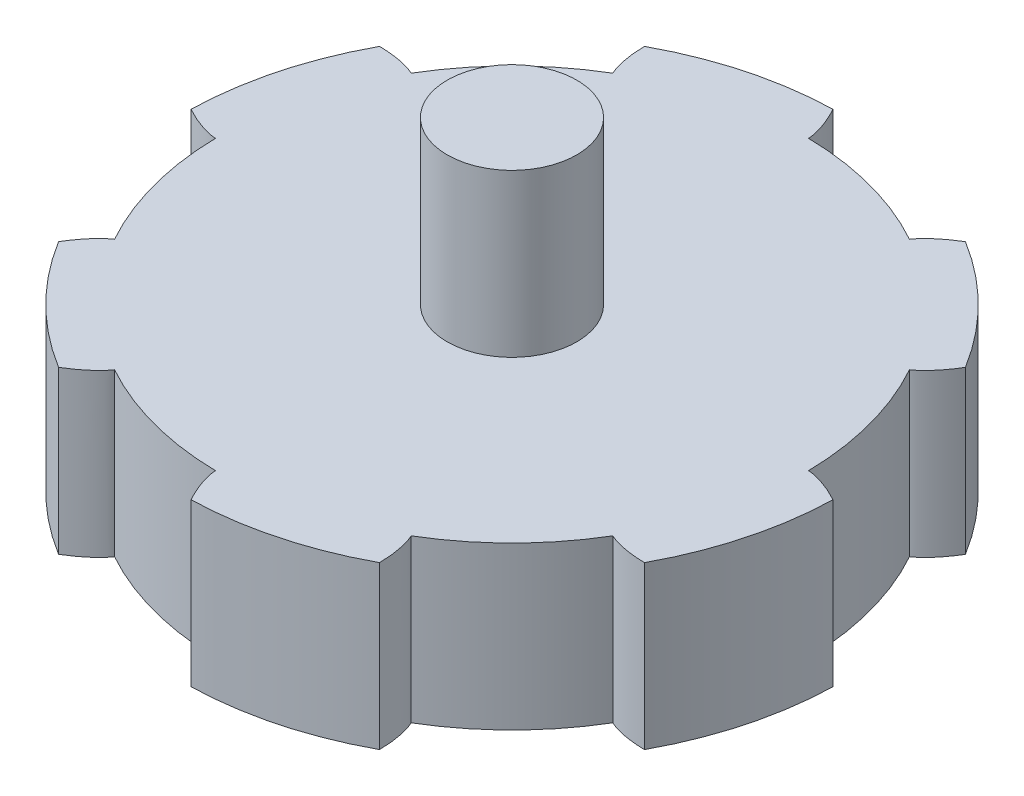
SolidWorks part; units mm, degrees
ref_plane "正面" through (0, 0, 0) normal (0, 0, 1) x (1, 0, 0)
ref_plane "平面" through (0, 0, 0) normal (0, 1, 0) x (1, 0, 0)
ref_plane "右側面" through (0, 0, 0) normal (1, 0, 0) x (0, 0, -1)
sketch "ｽｹｯﾁ1" plane through (0, 0, 0) normal (0, 1, 0) x (1, 0, 0)
  line L0 (0, 0) -> (0, 38.4) construction
  line L1 (-12.9461, 19.2) -> (11.294, 19.2) construction
  line L2 (-16.2445, 13.2875) -> (12.5124, 23.7541) construction
  line L3 (18.0421, 0) -> (19.2, 0) construction
  line L4 (19.2, 0) -> (20.3579, 0) construction
  circle A0 centre (0, 0) radius 19.2 construction
  circle A1 centre (0, 0) radius 18.0421
  circle A2 centre (0, 0) radius 20.3579 construction
  point P6 (0, 19.2)
  point P7 (0, 0)
  point P17 (-6.1708, 16.954)
  dimension "D1" = 38.4
  dimension "D2" = 20
sketch "ｽｹｯﾁ3" plane through (0, 0, 0) normal (0, 1, 0) x (1, 0, 0)
  line L0 (-6.1708, 16.954) -> (0, 19.2)
  line L1 (-7.1005, 16.5861) -> (-0.1443, 19.5641) construction
  line L2 (-8.0084, 16.1673) -> (-0.3318, 19.9699) construction
  line L3 (-8.8918, 15.6989) -> (-0.5675, 20.4137) construction
  line L4 (-9.7478, 15.1822) -> (-0.856, 20.8912) construction
  line L5 (-10.5739, 14.6188) -> (-1.2017, 21.3978) construction
  line L6 (-5.2221, 17.2698) -> (0.1064, 18.8811) construction
  line L7 (-4.2573, 17.5326) -> (0.1805, 18.6102) construction
  line L8 (-3.2795, 17.7415) -> (0.2278, 18.3899) construction
  line L9 (-2.2917, 17.896) -> (0.2543, 18.222) construction
  line L10 (-1.2968, 17.9954) -> (0.266, 18.108) construction
  line L11 (0, 0) -> (-10.763, 40.1682) construction
  line L12 (0, 0) -> (0, 38.4) construction
  arc A0 (-6.1708, 16.954) -> (-5.2221, 17.2698) centre (0, 0) cw
  arc A1 (-2.2917, 17.896) -> (-1.2968, 17.9954) centre (0, 0) cw
  arc A2 (-5.2221, 17.2698) -> (-4.2573, 17.5326) centre (0, 0) cw
  arc A3 (-4.2573, 17.5326) -> (-3.2795, 17.7415) centre (0, 0) cw
  arc A4 (-3.2795, 17.7415) -> (-2.2917, 17.896) centre (0, 0) cw
  arc A5 (-8.0084, 16.1673) -> (-8.8918, 15.6989) centre (0, 0) ccw
  arc A6 (-6.1708, 16.954) -> (-7.1005, 16.5861) centre (0, 0) ccw
  arc A7 (-7.1005, 16.5861) -> (-8.0084, 16.1673) centre (0, 0) ccw
  circle A8 centre (0, 0) radius 18.0421 construction
  arc A9 (-8.8918, 15.6989) -> (-9.7478, 15.1822) centre (0, 0) ccw
  arc A10 (-9.7478, 15.1822) -> (-10.5739, 14.6188) centre (0, 0) ccw
  arc A12 (-6.1708, 16.954) -> (0.2689, 18.0401) centre (0, 0) cw
  spline S0 degree 3 poles (-1.2017, 21.3978) (-0.973, 21.0814) (-0.6685, 20.6127) (-0.3361, 19.9884) (-0.1481, 19.5826) (-0.0032, 19.2185) (0.1038, 18.8996) (0.1783, 18.6287) (0.2262, 18.4084) (0.2567, 18.2181) (0.268, 18.101) (0.2689, 18.0401) knots 0 0 0 0 0.315921 0.451458 0.572046 0.677686 0.768377 0.844119 0.904913 0.950757 1 1 1 1
  spline S1 degree 3 poles (-9.6581, 19.1319) (-9.698, 18.7435) (-9.7275, 18.1854) (-9.7031, 17.4785) (-9.6631, 17.033) (-9.6065, 16.6453) (-9.5397, 16.3156) (-9.4688, 16.0438) (-9.4001, 15.829) (-9.3313, 15.649) (-9.2826, 15.5419) (-9.2529, 15.4887) knots 0 0 0 0 0.315921 0.451458 0.572046 0.677686 0.768377 0.844119 0.904913 0.950757 1 1 1 1
  point P54 (0, 0)
  dimension "D2" = 6.5668
  dimension "D3" = 7.5668
  dimension "D4" = 8.5668
  dimension "D5" = 9.5668
  dimension "D6" = 10.5668
  dimension "D7" = 11.5668
  dimension "D8" = 5.5668
  dimension "D9" = 4.5668
  dimension "D10" = 3.5668
  dimension "D11" = 2.5668
  dimension "D12" = 1.5668
  dimension "D14" = 15
  dimension "D1" = 1
  dimension "D13" = 6.5668
sketch "ｽｹｯﾁ4" plane through (0, 0, 0) normal (0, 1, 0) x (1, 0, 0)
  arc A0 (0.2689, 18.0401) -> (-9.2529, 15.4887) centre (0, 0) ccw
  arc A1 (-0.5322, 20.3509) -> (-9.7145, 17.8906) centre (0, 0) ccw
  spline S0 degree 3 poles (-1.2017, 21.3978) (-0.973, 21.0814) (-0.6685, 20.6127) (-0.3361, 19.9884) (-0.1481, 19.5826) (-0.0032, 19.2185) (0.1038, 18.8996) (0.1783, 18.6287) (0.2262, 18.4084) (0.2567, 18.2181) (0.268, 18.101) (0.2689, 18.0401) knots 0 0 0 0 0.315921 0.451458 0.572046 0.677686 0.768377 0.844119 0.904913 0.950757 1 1 1 1 construction
  spline S1 degree 3 poles (-0.5322, 20.3509) (-0.3901, 20.0953) (-0.2012, 19.716) (-0.0032, 19.2185) (0.1038, 18.8996) (0.1783, 18.6287) (0.2262, 18.4084) (0.2567, 18.2181) (0.268, 18.101) (0.2689, 18.0401) knots 0 0 0 0 0.356146 0.515081 0.651525 0.765478 0.856942 0.925915 1 1 1 1
  spline S2 degree 3 poles (-9.6581, 19.1319) (-9.698, 18.7435) (-9.7275, 18.1854) (-9.7031, 17.4785) (-9.6631, 17.033) (-9.6065, 16.6453) (-9.5397, 16.3156) (-9.4688, 16.0438) (-9.4001, 15.829) (-9.3313, 15.649) (-9.2826, 15.5419) (-9.2529, 15.4887) knots 0 0 0 0 0.315921 0.451458 0.572046 0.677686 0.768377 0.844119 0.904913 0.950757 1 1 1 1 construction
  spline S3 degree 3 poles (-9.7145, 17.8906) (-9.7098, 17.5981) (-9.6838, 17.1751) (-9.6065, 16.6453) (-9.5397, 16.3156) (-9.4688, 16.0438) (-9.4001, 15.829) (-9.3313, 15.649) (-9.2826, 15.5419) (-9.2529, 15.4887) knots 0 0 0 0 0.356146 0.515081 0.651525 0.765478 0.856942 0.925915 1 1 1 1
  point P6 (-0.5322, 20.3509)
  point P7 (-9.7145, 17.8906)
extrude "ﾎﾞｽ - 押し出し1" add sketch "ｽｹｯﾁ1" along normal blind 10
extrude "ﾎﾞｽ - 押し出し2" add sketch "ｽｹｯﾁ4" along normal blind 10
pattern_circular "円形ﾊﾟﾀｰﾝ1" count 6 over 360 about axis through (0, 10, 0) along (0, 1, 0) of "ﾎﾞｽ - 押し出し2"
sketch "ｽｹｯﾁ5" plane through (0, 10, 0) normal (0, 1, 0) x (1, 0, 0)
  circle A0 centre (0, 0) radius 4
  dimension "D1" = 8
extrude "ﾎﾞｽ - 押し出し3" add sketch "ｽｹｯﾁ5" along normal blind 10
equation "\"D3@ｽｹｯﾁ3\"=\"D2@ｽｹｯﾁ3\"+\"D1@ｽｹｯﾁ3\""
equation "\"D4@ｽｹｯﾁ3\"=\"D2@ｽｹｯﾁ3\"+2*\"D1@ｽｹｯﾁ3\""
equation "\"D5@ｽｹｯﾁ3\"=\"D2@ｽｹｯﾁ3\"+3"
equation "\"D6@ｽｹｯﾁ3\"=\"D2@ｽｹｯﾁ3\"+4"
equation "\"D7@ｽｹｯﾁ3\"=\"D2@ｽｹｯﾁ3\"+5"
equation "\"D8@ｽｹｯﾁ3\"=\"D2@ｽｹｯﾁ3\"-1"
equation "\"D9@ｽｹｯﾁ3\"=\"D2@ｽｹｯﾁ3\"-2"
equation "\"D10@ｽｹｯﾁ3\"=\"D2@ｽｹｯﾁ3\"-3"
equation "\"D11@ｽｹｯﾁ3\"=\"D2@ｽｹｯﾁ3\"-4"
equation "\"D12@ｽｹｯﾁ3\"=\"D2@ｽｹｯﾁ3\"-5"
equation "\"D13@ｽｹｯﾁ3\"=\"D2@ｽｹｯﾁ3\""
equation "\"D14@ｽｹｯﾁ3\"=90/6"
